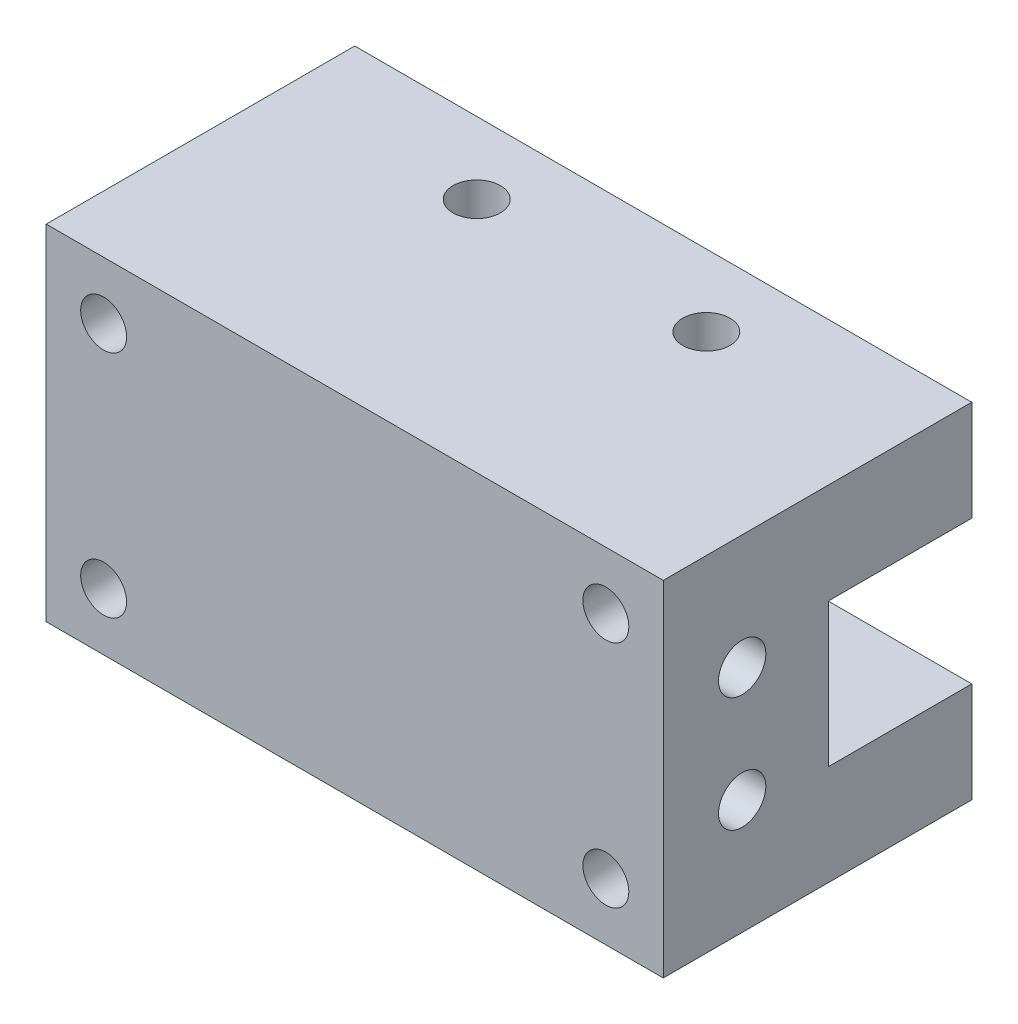
SolidWorks part; units mm, degrees
ref_plane "Front" through (0, 0, 0) normal (0, 0, 1) x (1, 0, 0)
ref_plane "Top" through (0, 0, 0) normal (0, 1, 0) x (1, 0, 0)
ref_plane "Right" through (0, 0, 0) normal (1, 0, 0) x (0, 0, -1)
sketch "草图1" plane through (0, 0, 0) normal (0, 0, 1) x (1, 0, 0)
  line L1 (21.5, 12) -> (-21.5, 12)
  line L2 (21.5, 12) -> (21.5, -12)
  line L3 (21.5, -12) -> (-21.5, -12)
  line L4 (-21.5, 12) -> (-21.5, -12)
  line L5 (21.5, 12) -> (-21.5, -12) construction
  line L6 (21.5, -12) -> (-21.5, 12) construction
  line L7 (17.5, 8) -> (-17.5, 8) construction
  line L8 (17.5, 8) -> (17.5, -8) construction
  line L9 (17.5, -8) -> (-17.5, -8) construction
  line L10 (-17.5, 8) -> (-17.5, -8) construction
  line L11 (17.5, 8) -> (-17.5, -8) construction
  line L12 (17.5, -8) -> (-17.5, 8) construction
  circle A0 centre (-17.5, 8) radius 1.6
  circle A1 centre (-17.5, -8) radius 1.6
  circle A2 centre (17.5, -8) radius 1.6
  circle A3 centre (17.5, 8) radius 1.6
  point P0 (0, 0)
  point P6 (0, 0)
  dimension "D5" = 3.2
  dimension "D1" = 35
  dimension "D2" = 16
  dimension "D3" = 43
  dimension "D4" = 24
extrude "凸台-拉伸1" add sketch "草图1" along normal blind 11.5
sketch "草图2" plane through (0, 0, 11.5) normal (0, 0, 1) x (1, 0, 0)
  circle A0 centre (-17.5, 8) radius 2.75
  circle A1 centre (-17.5, -8) radius 2.75
  circle A2 centre (17.5, -8) radius 2.75
  circle A3 centre (17.5, 8) radius 2.75
  dimension "D1" = 5.5
sketch "草图3" plane through (0, 0, 0) normal (0, 0, -1) x (-1, 0, 0)
  line L0 (-21.5, -12) -> (-21.5, 12) construction
  line L1 (21.5, -12) -> (-21.5, -12)
  line L2 (21.5, -12) -> (21.5, -5)
  line L3 (21.5, -5) -> (-21.5, -5)
  line L4 (-21.5, -12) -> (-21.5, -5)
  line L6 (21.5, 12) -> (-21.5, 12)
  line L7 (21.5, 12) -> (21.5, 5)
  line L8 (21.5, 5) -> (-21.5, 5)
  line L9 (-21.5, 12) -> (-21.5, 5)
  circle A0 centre (17.5, 8) radius 2.75 construction
  circle A1 centre (-17.5, 8) radius 2.75 construction
  circle A2 centre (-17.5, -8) radius 2.75 construction
  circle A3 centre (17.5, -8) radius 2.75 construction
  circle A4 centre (17.5, 8) radius 2.75
  circle A5 centre (-17.5, 8) radius 2.75
  circle A6 centre (-17.5, -8) radius 2.75
  circle A7 centre (17.5, -8) radius 2.75
  dimension "D1" = 5
  dimension "D2" = 5
extrude "凸台-拉伸2" add sketch "草图3" along normal blind 10
sketch "草图4" plane through (0, 12, 0) normal (0, 1, 0) x (1, 0, 0)
  line L0 (0, 0) -> (0, 5) construction
  line L1 (0, 5) -> (8, 5) construction
  circle A0 centre (8, 5) radius 2.1
  circle A1 centre (-8, 5) radius 2.1
  dimension "D1" = 4.2
  dimension "D2" = 5
  dimension "D3" = 8
extrude "切除-拉伸1" cut sketch "草图4" against normal blind 10 from offset 15 offset against normal yes
hole_wizard "M4 螺纹孔1" positions "草图5" profile "草图6" tap size "M4" standard "GB"
sketch "草图5" plane through (0, 12, 0) normal (0, 1, 0) x (1, 0, 0)
  point P0 (-8, 5)
  point P3 (8, 5)
sketch "草图6" plane through (-8, 12, -5) normal (1, 0, 0) x (0, 0, 1)
  line L0 (0, 0) -> (0, 11.0914)
  line L1 (0, 11.0914) -> (1.65, 10.1)
  line L2 (1.65, 10.1) -> (1.65, 0)
  line L5 (1.65, 0) -> (0, 0)
  line L10 (0, 11.0914) -> (-1.65, 10.1) construction
  line L11 (0, -6.35) -> (0, 107.95) construction
  dimension "螺纹孔钻头直径" = 3.3
  dimension "螺纹孔钻头深度" = 10.1
  dimension "导头角度" = 118
cosmetic thread "孔螺蚊线1" parameters "D1"=7, "D2"=4
cosmetic thread "孔螺蚊线2" parameters "D1"=7, "D2"=4
sketch "草图7" plane through (21.5, 0, 0) normal (1, 0, 0) x (0, 0, -1)
  line L0 (0, 0) -> (-6, 0) construction
  line L1 (-6, 0) -> (-6, 4) construction
  line L2 (10, 12) -> (10, 5) construction
  circle A0 centre (-6, 4) radius 1.5
  circle A1 centre (-6, -4) radius 1.5
  dimension "D1" = 3
  dimension "D2" = 16
  dimension "D3" = 4
hole_wizard "M4 螺纹孔2" positions "3D草图1" profile "草图8" tap size "M4" standard "GB"
sketch3d "3D草图1"
  point P0 (21.5, 4, 6)
  point P3 (21.5, -4, 6)
sketch "草图8" plane through (21.5, 4, 6) normal (0, 1, 0) x (0, 0, -1)
  line L0 (0, 0) -> (0, 11.0914)
  line L1 (0, 11.0914) -> (1.65, 10.1)
  line L2 (1.65, 10.1) -> (1.65, 0)
  line L5 (1.65, 0) -> (0, 0)
  line L10 (0, 11.0914) -> (-1.65, 10.1) construction
  line L11 (0, -6.35) -> (0, 107.95) construction
  dimension "螺纹孔钻头直径" = 3.3
  dimension "螺纹孔钻头深度" = 10.1
  dimension "导头角度" = 118
cosmetic thread "孔螺蚊线3" parameters "D1"=8, "D2"=4
cosmetic thread "孔螺蚊线4" parameters "D1"=8, "D2"=4
